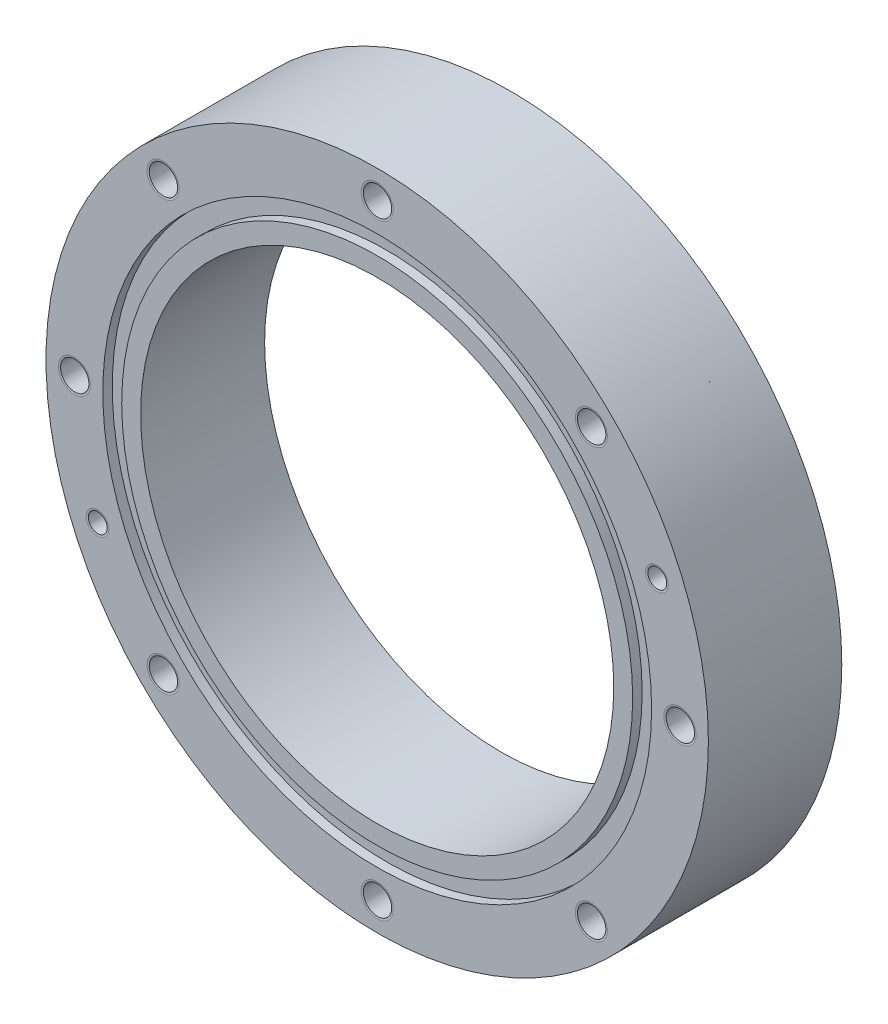
SolidWorks part; units mm, degrees
ref_plane "Front Plane" through (0, 0, 0) normal (0, 0, 1) x (1, 0, 0)
ref_plane "Top Plane" through (0, 0, 0) normal (0, 1, 0) x (1, 0, 0)
ref_plane "Right Plane" through (0, 0, 0) normal (1, 0, 0) x (0, 0, -1)
sketch "Croquis1" plane through (0, 0, 0) normal (0, 0, 1) x (1, 0, 0)
  circle A0 centre (0, 0) radius 35
  circle A1 centre (0, 32) radius 1.5
  circle A2 centre (22.6274, 22.6274) radius 1.5
  circle A3 centre (32, 0) radius 1.5
  circle A4 centre (22.6274, -22.6274) radius 1.5
  circle A5 centre (0, -32) radius 1.5
  circle A6 centre (-22.6274, -22.6274) radius 1.5
  circle A7 centre (-32, 0) radius 1.5
  circle A8 centre (-22.6274, 22.6274) radius 1.5
  circle A9 centre (0, 0) radius 29
  point P21 (0, 0)
  dimension "D1" = 8
extrude "Saliente-Extruir3" add sketch "Croquis1" along normal blind 14.1
sketch "Croquis4" plane through (0, 0, 0) normal (0, 0, -1) x (-1, 0, 0)
  circle A0 centre (0, 0) radius 25
  circle A1 centre (0, 0) radius 29
extrude "Saliente-Extruir4" add sketch "Croquis4" against normal blind 14.1 separate body
sketch "Croquis5" plane through (0, 0, 0) normal (0, 0, -1) x (-1, 0, 0)
  circle A0 centre (0, 0) radius 29
extrude "Cortar-Extruir1" cut sketch "Croquis5" against normal blind 1.1 draft 76
sketch "Croquis6" plane through (0, 0, 14.1) normal (0, 0, 1) x (1, 0, 0)
  circle A0 centre (0, 0) radius 29
  circle A1 centre (0, 0) radius 25
extrude "Saliente-Extruir5" add sketch "Croquis6" against normal blind 3.1
sketch "Croquis7" plane through (0, 0, 14.1) normal (0, 0, 1) x (1, 0, 0)
  circle A0 centre (0, 0) radius 29
  circle A1 centre (0, 0) radius 27
extrude "Cortar-Extruir2" cut sketch "Croquis7" against normal blind 1
sketch "Croquis9" plane through (0, 0, 0) normal (0, 0, -1) x (-1, 0, 0)
  circle A0 centre (0, 32) radius 1.7
  circle A1 centre (22.6274, 22.6274) radius 1.7
  circle A2 centre (32, 0) radius 1.7
  circle A3 centre (22.6274, -22.6274) radius 1.7
  circle A4 centre (0, -32) radius 1.7
  circle A5 centre (-22.6274, -22.6274) radius 1.7
  circle A6 centre (-32, 0) radius 1.7
  circle A7 centre (-22.6274, 22.6274) radius 1.7
  point P20 (0, 0)
  dimension "D1" = 8
extrude "Cortar-Extruir3" cut sketch "Croquis9" against normal blind 1 draft 80
sketch "Croquis10" plane through (0, 0, 14.1) normal (0, 0, 1) x (1, 0, 0)
  circle A0 centre (0, 32) radius 1.7
  circle A1 centre (22.6274, 22.6274) radius 1.7
  circle A2 centre (32, 0) radius 1.7
  circle A3 centre (22.6274, -22.6274) radius 1.7
  circle A4 centre (0, -32) radius 1.7
  circle A5 centre (-22.6274, -22.6274) radius 1.7
  circle A6 centre (-32, 0) radius 1.7
  circle A7 centre (-22.6274, 22.6274) radius 1.7
  point P19 (0, 0)
  dimension "D1" = 8
extrude "Cortar-Extruir4" cut sketch "Croquis10" against normal blind 1 draft 80
sketch "Croquis11" plane through (0, 0, 14.1) normal (0, 0, 1) x (1, 0, 0)
  circle A0 centre (29.5641, 12.2459) radius 1
  circle A1 centre (-29.5641, -12.2459) radius 1
extrude "Cortar-Extruir5" cut sketch "Croquis11" against normal blind 4
sketch "Croquis12" plane through (0, 0, 14.1) normal (0, 0, 1) x (1, 0, 0)
  circle A0 centre (29.5641, 12.2459) radius 1.2
  circle A1 centre (-29.5641, -12.2459) radius 1.2
extrude "Cortar-Extruir6" cut sketch "Croquis12" against normal blind 4 draft 80
